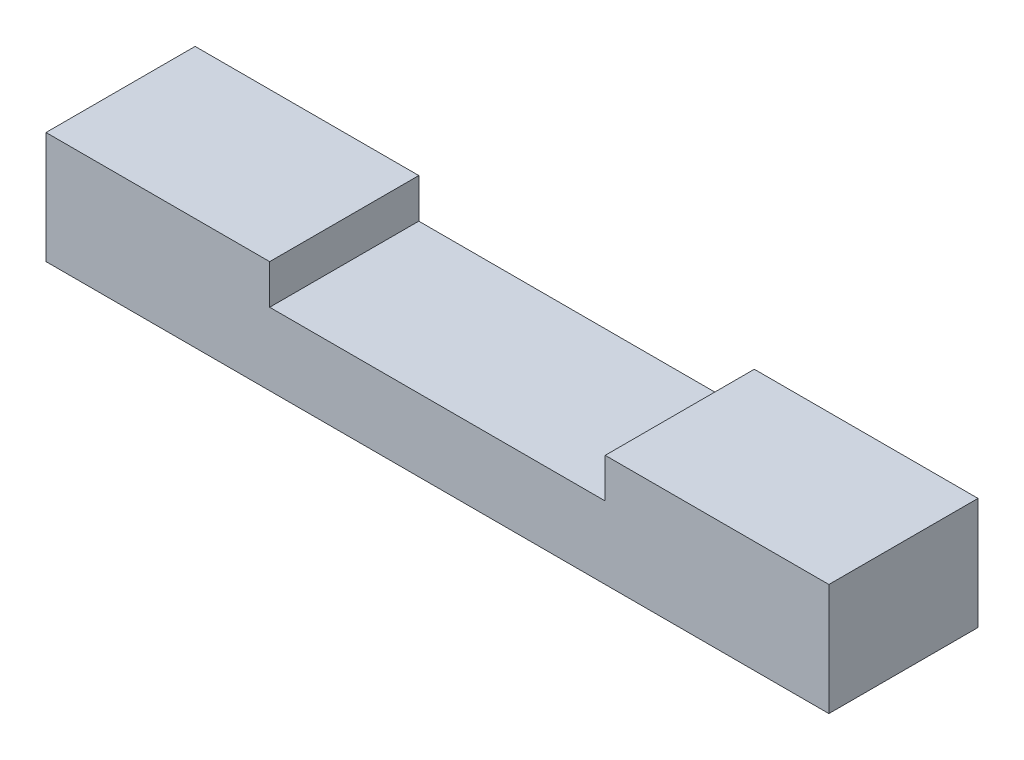
SolidWorks part; units mm, degrees
ref_plane "前视基准面" through (0, 0, 0) normal (0, 0, 1) x (1, 0, 0)
ref_plane "上视基准面" through (0, 0, 0) normal (0, 1, 0) x (1, 0, 0)
ref_plane "右视基准面" through (0, 0, 0) normal (1, 0, 0) x (0, 0, -1)
sketch "草图1" plane through (0, 0, 0) normal (0, 0, 1) x (1, 0, 0)
  line L0 (0, 0) -> (1050, 0)
  line L1 (1050, 0) -> (1050, 150)
  line L2 (1050, 150) -> (750, 150)
  line L3 (750, 150) -> (750, 97)
  line L4 (750, 97) -> (300, 97)
  line L5 (300, 97) -> (300, 150)
  line L6 (300, 150) -> (0, 150)
  line L7 (0, 150) -> (0, 0)
  dimension "D1" = 1050
  dimension "D2" = 450
  dimension "D3" = 150
  dimension "D4" = 53
extrude "凸台-拉伸1" add sketch "草图1" along normal blind 200
